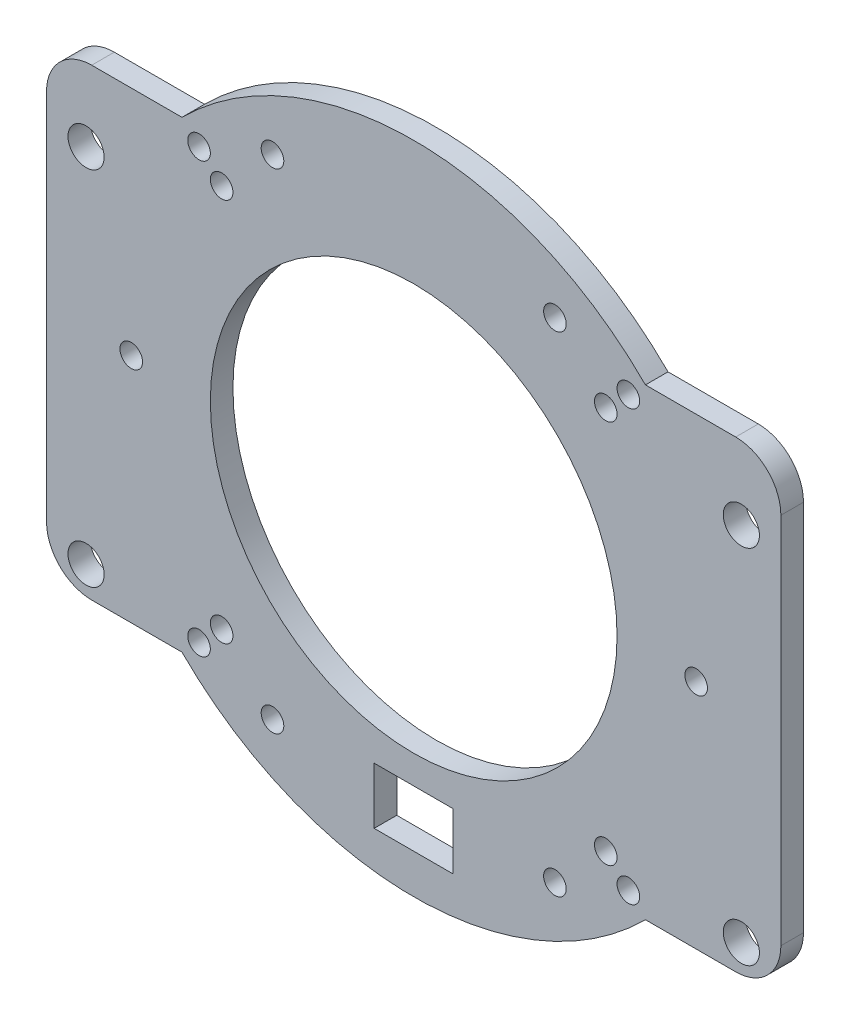
SolidWorks part; units mm, degrees
ref_plane "Front Plane" through (0, 0, 0) normal (0, 0, 1) x (1, 0, 0)
ref_plane "Top Plane" through (0, 0, 0) normal (0, 1, 0) x (1, 0, 0)
ref_plane "Right Plane" through (0, 0, 0) normal (1, 0, 0) x (0, 0, -1)
sketch "Sketch1" plane through (0, 0, 0) normal (0, 0, 1) x (1, 0, 0)
  line L0 (-32.5, 20.5) -> (-20.5122, 20.5)
  line L1 (32.5, 20.5) -> (32.5, -20.5)
  line L2 (32.5, -20.5) -> (20.5122, -20.5)
  line L3 (-32.5, -20.5) -> (-32.5, 20.5)
  line L4 (0, 39) -> (0, -40.7055) construction
  line L5 (-43.0364, 0) -> (51.1093, 0) construction
  line L6 (20.5122, 20.5) -> (32.5, 20.5)
  line L7 (-20.5122, -20.5) -> (-32.5, -20.5)
  arc A0 (-20.5122, -20.5) -> (20.5122, -20.5) centre (0, 0) ccw
  arc A1 (20.5122, 20.5) -> (-20.5122, 20.5) centre (0, 0) ccw
  circle A2 centre (0, 0) radius 18
  point P12 (26.5061, 20.5)
  dimension "D1" = 58
  dimension "D4" = 36
  dimension "D2" = 65
  dimension "D3" = 41
extrude "Boss-Extrude1" add sketch "Sketch1" along normal blind 2
sketch "Sketch2" plane through (0, 0, 2) normal (0, 0, 1) x (1, 0, 0)
  line L0 (-37.3479, -2) -> (38.9026, -2) construction
  line L1 (0, 32.4479) -> (0, -34.6372) construction
  line L2 (-7.3141, 0) -> (5.8301, 0) construction
  circle A0 centre (-29, 14) radius 1.6
  circle A1 centre (-29, -18) radius 1.6
  circle A2 centre (29, -18) radius 1.6
  circle A3 centre (29, 14) radius 1.6
  dimension "D1" = 3.2
  dimension "D2" = 58
  dimension "D3" = 32
  dimension "D4" = 2
extrude "Cut-Extrude1" cut sketch "Sketch2" against normal blind 2
sketch "Sketch3" plane through (0, 0, 2) normal (0, 0, 1) x (1, 0, 0)
  line L0 (0, 15.6309) -> (0, -13.6849) construction
  line L1 (-12.5553, 0) -> (11.836, 0) construction
  point P5 (-17, 17)
  point P6 (17, 17)
  point P7 (17, -17)
  point P8 (-17, -17)
  point P9 (19, 19)
  point P10 (19, -19)
  point P11 (-19, -19)
  point P13 (-19, 19)
  dimension "D1" = 34
  dimension "D2" = 34
  dimension "D3" = 38
  dimension "D4" = 38
hole_wizard "Ø2.0mm Dowel Hole1" positions "3DSketch1" profile "Sketch4" hole size "Ø2.0" standard "ANSI Metric" end condition through all
sketch3d "3DSketch1"
  point P0 (-19, 19, 2)
  point P3 (-17, 17, 2)
  point P6 (17, 17, 2)
  point P9 (19, 19, 2)
  point P12 (17, -17, 2)
  point P15 (19, -19, 2)
  point P18 (-19, -19, 2)
  point P21 (-17, -17, 2)
sketch "Sketch4" plane through (-19, 19, 2) normal (1, 0, 0) x (0, -1, 0)
  line L0 (0, 0) -> (0, 2)
  line L1 (0, 2) -> (1, 2)
  line L2 (1, 2) -> (1, 0)
  line L5 (1, 0) -> (0, 0)
  line L11 (0, -6.35) -> (0, 107.95) construction
  dimension "Thru Hole Dia." = 2
  dimension "Thru Hole Depth" = 2
sketch "Sketch5" plane through (0, 0, 0) normal (0, 0, -1) x (-1, 0, 0)
  line L0 (12.5, 21.6506) -> (12.5, -21.6506) construction
  line L1 (12.5, -21.6506) -> (-25, 0) construction
  line L2 (0, 0) -> (14.1533, 0) construction
  line L3 (0, 0) -> (0, 14.1167) construction
  line L4 (0, 15.6309) -> (0, -13.6849) construction
  line L5 (-25, 0) -> (12.5, 21.6506) construction
  line L6 (12.5, -21.6506) -> (0, 0) construction
  line L7 (0, 0) -> (-25, 0) construction
  line L8 (12.5, 21.6506) -> (0, 0) construction
  line L9 (25, 0) -> (0, 0) construction
  line L10 (0, 0) -> (-12.5, 21.6506) construction
  line L11 (0, 0) -> (-12.5, -21.6506) construction
  line L12 (25, 0) -> (-12.5, 21.6506) construction
  line L13 (-12.5, 21.6506) -> (-12.5, -21.6506) construction
  line L14 (-12.5, -21.6506) -> (25, 0) construction
  dimension "D2" = 60
  dimension "D3" = 60
  dimension "D4" = 25
fillet "Fillet1" radius 4 4 edges at (-32.5, -20.5, 1) (-32.5, 20.5, 1) (32.5, 20.5, 1) (32.5, -20.5, 1)
sketch "스케치1" plane through (0, 0, 0) normal (0, 0, -1) x (-1, 0, 0)
  line L0 (3.5, -20.5) -> (-3.5, -25.5) construction
  line L1 (-3.5, -20.5) -> (3.5, -20.5)
  line L2 (-3.5, -20.5) -> (-3.5, -25.5)
  line L3 (-3.5, -25.5) -> (3.5, -25.5)
  line L4 (3.5, -20.5) -> (3.5, -25.5)
  line L5 (0, 0) -> (0, -31.5532) construction
  point P7 (0, -23)
  point P8 (0, 0)
  point P9 (3.5, -23)
  dimension "D1" = 7
  dimension "D2" = 5
  dimension "D3" = 23
extrude "컷-돌출1" cut sketch "스케치1" against normal through all
hole_wizard "Ø2.0mm 맞춤핀 구멍1" positions "3D스케치2" profile "스케치3" hole size "Ø2.0" standard "Ansi Metric" end condition through all
sketch3d "3D스케치2"
  point P0 (12.5, 21.6506, 0)
  point P3 (-12.5, 21.6506, 0)
  point P6 (-25, 0, 0)
  point P9 (-12.5, -21.6506, 0)
  point P12 (12.5, -21.6506, 0)
  point P15 (25, 0, 0)
sketch "스케치3" plane through (12.5, 21.6506, 0) normal (1, 0, 0) x (0, 1, 0)
  line L0 (0, 0) -> (0, 2)
  line L1 (0, 2) -> (1, 2)
  line L2 (1, 2) -> (1, 0)
  line L5 (1, 0) -> (0, 0)
  line L11 (0, -6.35) -> (0, 107.95) construction
  dimension "관통 구멍 지름" = 2
  dimension "관통 구멍 깊이" = 2
